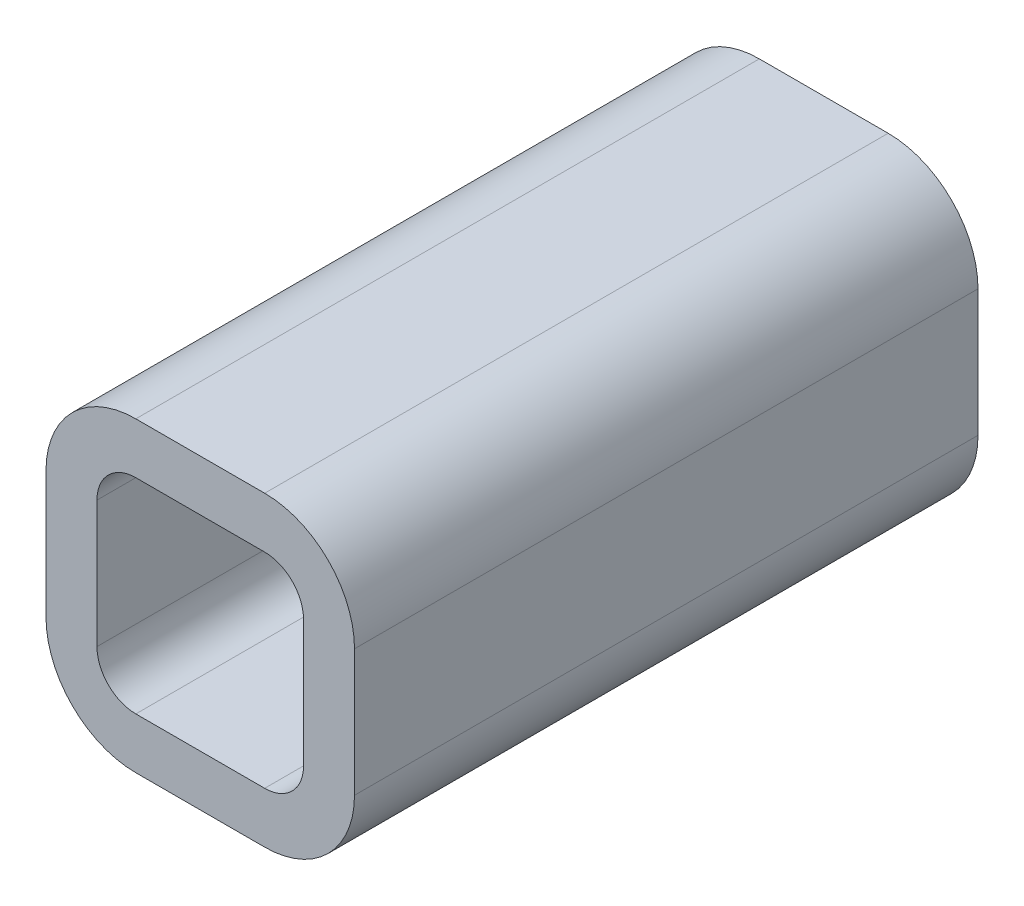
SolidWorks part; units mm, degrees
ref_plane "Front Plane" through (0, 0, 0) normal (0, 0, 1) x (1, 0, 0)
ref_plane "Top Plane" through (0, 0, 0) normal (0, 1, 0) x (1, 0, 0)
ref_plane "Right Plane" through (0, 0, 0) normal (1, 0, 0) x (0, 0, -1)
sketch "Sketch1" plane through (0, 0, 0) normal (0, 0, 1) x (1, 0, 0)
  line L4 (3.7084, 3) -> (3.7084, -3)
  line L5 (5.3084, 3) -> (5.3084, -3)
  line L6 (4.2084, 3.5) -> (4.8084, 3.5)
  line L7 (4.2084, -3.5) -> (4.8084, -3.5)
  line L8 (-1.71, 8.48) -> (5.42, 8.48)
  line L9 (-6.68, 3.51) -> (-6.68, -3.51)
  line L10 (-1.71, -8.48) -> (5.42, -8.48)
  line L11 (10.39, 3.51) -> (10.39, -3.51)
  circle A4 centre (0, 0) radius 1.7
  arc A5 (5.3084, 3) -> (4.8084, 3.5) centre (4.8084, 3) ccw
  arc A6 (3.7084, -3) -> (4.2084, -3.5) centre (4.2084, -3) ccw
  arc A7 (4.8084, -3.5) -> (5.3084, -3) centre (4.8084, -3) ccw
  arc A8 (5.42, 8.48) -> (10.39, 3.51) centre (5.42, 3.51) cw
  arc A9 (5.42, -8.48) -> (10.39, -3.51) centre (5.42, -3.51) ccw
  arc A10 (-6.68, -3.51) -> (-1.71, -8.48) centre (-1.71, -3.51) ccw
  arc A11 (-1.71, 8.48) -> (-6.68, 3.51) centre (-1.71, 3.51) ccw
  arc A12 (4.2084, 3.5) -> (3.7084, 3) centre (4.2084, 3) ccw
extrude "Boss-Extrude1" add sketch "Sketch1" along normal blind 34.5
sketch "Sketch2" plane through (0, 0, 34.5) normal (0, 0, 1) x (1, 0, 0)
  line L0 (7.57, -3.51) -> (7.57, 3.51)
  line L1 (-1.71, -5.66) -> (5.42, -5.66)
  line L2 (-3.86, 3.51) -> (-3.86, -3.51)
  line L3 (5.42, 5.66) -> (-1.71, 5.66)
  arc A0 (-1.71, -5.66) -> (-3.86, -3.51) centre (-1.71, -3.51) cw
  arc A1 (-3.86, 3.51) -> (-1.71, 5.66) centre (-1.71, 3.51) cw
  arc A2 (5.42, 5.66) -> (7.57, 3.51) centre (5.42, 3.51) cw
  arc A3 (7.57, -3.51) -> (5.42, -5.66) centre (5.42, -3.51) cw
extrude "Cut-Extrude1" cut sketch "Sketch2" against normal offset from surface (20.5 mm away) 14 up to face at (1.855, 0, 0)
sketch "Sketch3" plane through (0, 0, 14) normal (0, 0, 1) x (1, 0, 0)
  line L0 (5.5084, 3.5) -> (4.2084, 3.5)
  line L1 (6.0084, 3) -> (6.0084, -3)
  line L2 (5.5084, -3.5) -> (4.2084, -3.5)
  line L3 (3.7084, 3) -> (3.7084, -3)
  arc A0 (5.5084, 3.5) -> (6.0084, 3) centre (5.5084, 3) cw
  arc A1 (6.0084, -3) -> (5.5084, -3.5) centre (5.5084, -3) cw
  arc A2 (4.2084, -3.5) -> (3.7084, -3) centre (4.2084, -3) cw
  arc A3 (4.2084, 3.5) -> (3.7084, 3) centre (4.2084, 3) ccw
extrude "Cut-Extrude2" cut sketch "Sketch3" against normal offset from surface (7 mm away) 7 up to face at (1.855, 0, 0)
